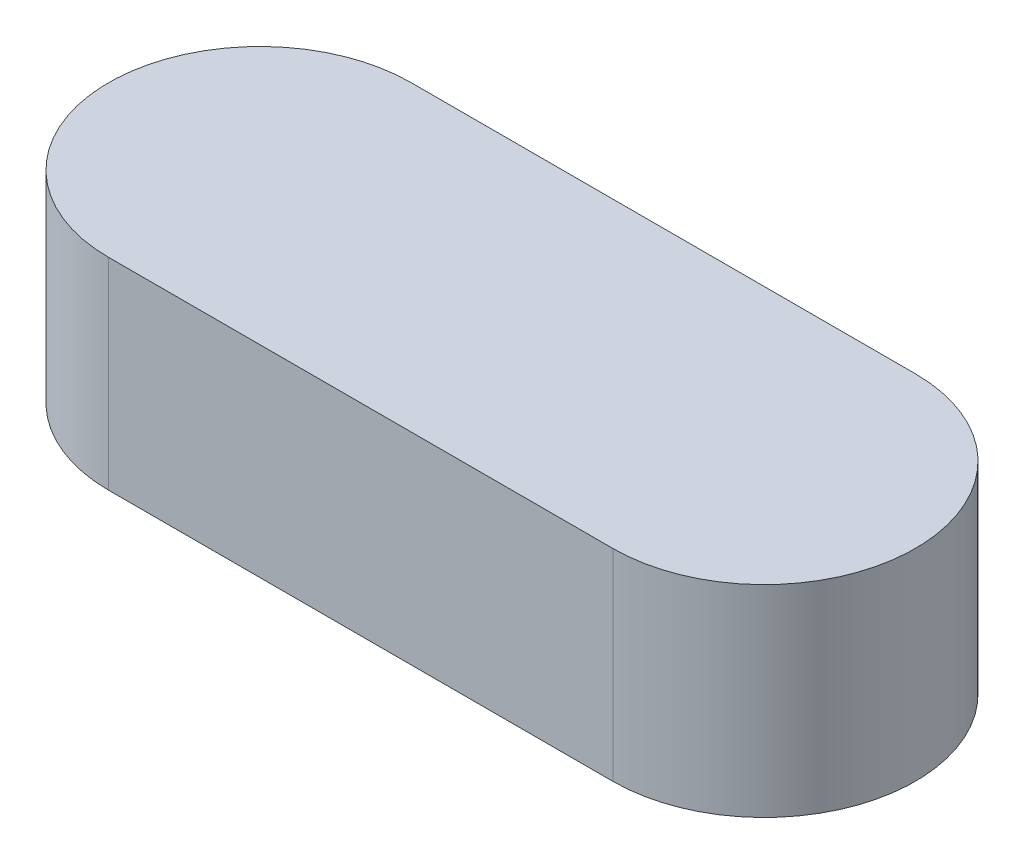
SolidWorks part; units mm, degrees
ref_plane "Front Plane" through (0, 0, 0) normal (0, 0, 1) x (1, 0, 0)
ref_plane "Top Plane" through (0, 0, 0) normal (0, 1, 0) x (1, 0, 0)
ref_plane "Right Plane" through (0, 0, 0) normal (1, 0, 0) x (0, 0, -1)
sketch "Sketch2" plane through (0, 0, 0) normal (0, 1, 0) x (1, 0, 0)
  line L0 (-4, 7.8286) -> (16, 7.8286)
  line L1 (16, -4.1714) -> (-4, -4.1714)
  arc A0 (16, 7.8286) -> (16, -4.1714) centre (16, 1.8286) cw
  arc A1 (-4, -4.1714) -> (-4, 7.8286) centre (-4, 1.8286) cw
  point P6 (-10, 1.8286)
  point P7 (22, 1.8286)
  dimension "D1" = 12
  dimension "D2" = 32
extrude "Boss-Extrude1" add sketch "Sketch2" along normal blind 8
